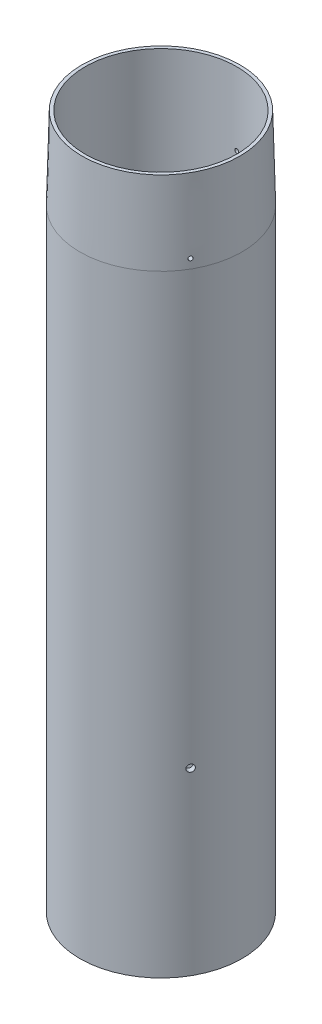
SolidWorks part; units mm, degrees
material "S1D_75 Degrees Custom Wound Fiberglass"
ref_plane "Front Plane" through (0, 0, 0) normal (0, 0, 1) x (1, 0, 0)
ref_plane "Top Plane" through (0, 0, 0) normal (0, 1, 0) x (1, 0, 0)
ref_plane "Right Plane" through (0, 0, 0) normal (1, 0, 0) x (0, 0, -1)
ref_axis "Axis1" through (0, -55, 0) along (0, 1, 0)
sketch "Sketch1" plane through (0, 0, 0) normal (0, 1, 0) x (1, 0, 0)
  circle A0 centre (0, 0) radius 38.1508
  circle A1 centre (0, 0) radius 40.8178
  dimension "D1" = 76.3016
  dimension "D2" = 2.667
extrude "Boss-Extrude1" add sketch "Sketch1" along normal blind 349.25
chamfer "Sanding Chamfer" distance 41.275 angle 1.45 1 edges at (0, 349.25, 40.8178)
ref_plane "Airframe Bolt Plane" through (35.3493, 0, 20.4089) normal (0.866, 0, 0.5) x (0, -1, 0)
sketch "Sketch2" plane through (35.3493, 0, 20.4089) normal (0.866, 0, 0.5) x (0, -1, 0)
  circle A0 centre (-90.4875, 0) radius 1.778
  dimension "D2" = 3.556
  dimension "D1" = 90.4875
extrude "Airframe Bolt Cut" cut sketch "Sketch2" against normal up to next
pattern_circular "Airframe Bolt Pattern" count 3 over 360 about axis through (0, -55, 0) along (0, 1, 0) of "Airframe Bolt Cut"
ref_plane "Shear Pin Plane" through (35.3493, 0, 20.4089) normal (0.866, 0, 0.5) x (0, -1, 0)
sketch "Sketch3" plane through (35.3493, 0, 20.4089) normal (0.866, 0, 0.5) x (0, -1, 0)
  line L0 (-349.25, 40.8178) -> (-349.25, -40.8178) construction
  circle A0 centre (-312.5216, 0) radius 0.9906
  dimension "D1" = 1.9812
  dimension "D2" = 36.7284
extrude "Shear Pin Cut" cut sketch "Sketch3" against normal up to next
pattern_circular "Shear Pin Pattern" count 3 over 360 about axis through (0, -55, 0) along (0, 1, 0) of "Shear Pin Cut"
equation "\"D2@Sketch3\"=2.892/2"
